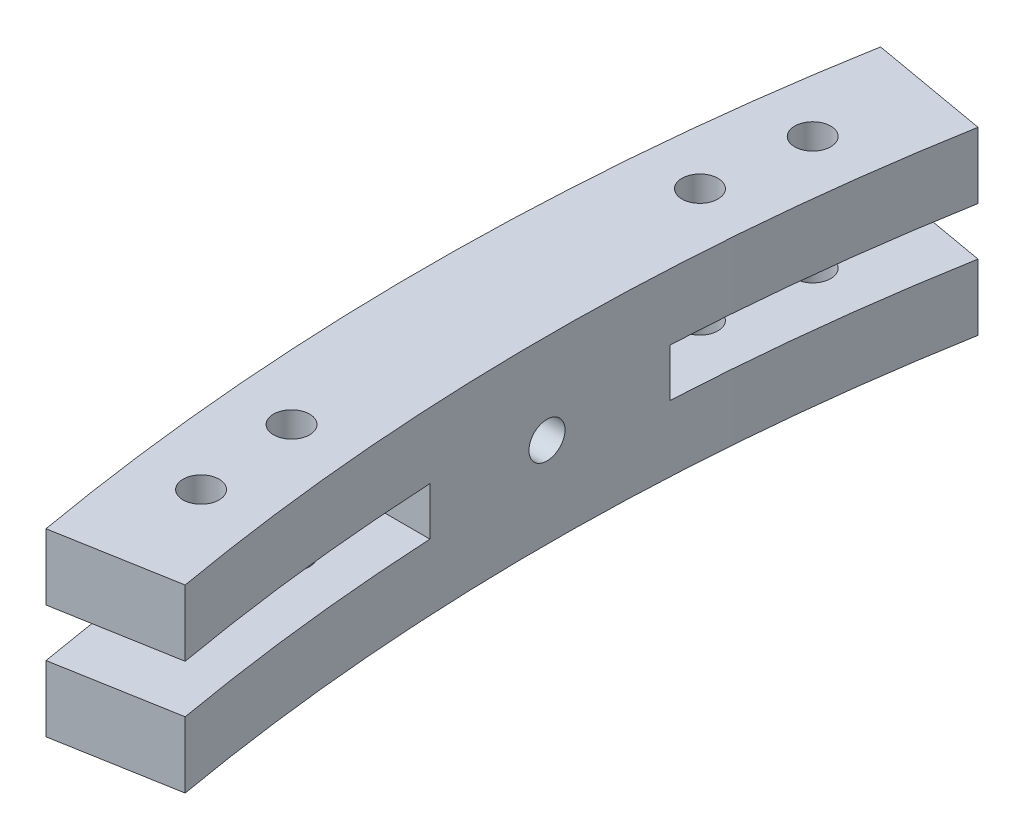
SolidWorks part; units mm, degrees
ref_plane "Front Plane" through (0, 0, 0) normal (0, 0, 1) x (1, 0, 0)
ref_plane "Top Plane" through (0, 0, 0) normal (0, 1, 0) x (1, 0, 0)
ref_plane "Right Plane" through (0, 0, 0) normal (1, 0, 0) x (0, 0, -1)
sketch "Sketch1" plane through (0, 0, 0) normal (0, 0, 1) x (1, 0, 0)
  line L0 (190, 0) -> (-190, 0) construction
  line L1 (0, 190) -> (0, -190) construction
  line L2 (0, 0) -> (-187.1135, 32.9932) construction
  line L3 (0, 0) -> (-187.1135, -32.9932) construction
  line L4 (-187.1135, 32.9932) -> (-196.9616, 34.7296)
  line L5 (-187.1135, -32.9932) -> (-196.9616, -34.7296)
  arc A0 (-187.1135, 32.9932) -> (-187.1135, -32.9932) centre (0, 0) ccw
  arc A1 (-196.9616, 34.7296) -> (-196.9616, -34.7296) centre (0, 0) ccw
  circle A3 centre (0, 0) radius 190 construction
  dimension "D1" = 380
  dimension "D2" = 10
  dimension "D3" = 20
sketch "Sketch9" plane through (0, 0, 0) normal (0, 1, 0) x (1, 0, 0)
  line L0 (0, 0) -> (-196.9616, 34.7296)
  line L1 (-200, 0) -> (200, 0) construction
  line L2 (0, 0) -> (-196.9616, -34.7296)
  circle A0 centre (0, 0) radius 195 construction
  circle A1 centre (0, 0) radius 195 construction
  circle A8 centre (0, 0) radius 200 construction
  circle A9 centre (0, 0) radius 190 construction
  circle A10 centre (0, 0) radius 200
  circle A11 centre (0, 0) radius 190
  dimension "D1" = 20
extrude "base" add sketch "Sketch9" along normal mid plane 15 contours A11 L0 A10 L2
sketch "Sketch11" plane through (0, 0, 0) normal (0, 1, 0) x (1, 0, 0)
  line L8 (-189.7367, -10) -> (-199.7498, -10) construction
  line L9 (-187.1135, -32.9932) -> (-196.9616, -34.7296) construction
  line L10 (-189.7367, 10) -> (-199.7498, 10) construction
  line L11 (-187.1135, 32.9932) -> (-196.9616, 34.7296) construction
  line L12 (-189.7367, -10) -> (-199.7498, -10)
  line L13 (-187.1135, -32.9932) -> (-196.9616, -34.7296)
  line L14 (-189.7367, 10) -> (-199.7498, 10)
  line L15 (-187.1135, 32.9932) -> (-196.9616, 34.7296)
  circle A14 centre (0, 0) radius 200 construction
  circle A15 centre (0, 0) radius 190 construction
  arc A16 (-196.9616, 34.7296) -> (-199.7498, 10) centre (0, 0) ccw
  arc A17 (-187.1135, 32.9932) -> (-189.7367, 10) centre (0, 0) ccw
  arc A18 (-199.7498, -10) -> (-196.9616, -34.7296) centre (0, 0) ccw
  arc A19 (-189.7367, -10) -> (-187.1135, -32.9932) centre (0, 0) ccw
extrude "mount" cut sketch "Sketch11" along normal up to surface and the other way up to surface
sketch "Sketch12" plane through (0, 0, 0) normal (0, 1, 0) x (1, 0, 0)
  line L0 (-200, 0) -> (200, 0) construction
  line L1 (-200, 0) -> (200, 0) construction
  line L2 (0, 0) -> (-193.3317, 25.4526) construction
  line L3 (0, 0) -> (-194.258, 16.9954) construction
  line L4 (0, 0) -> (-194.258, -16.9954) construction
  line L5 (0, 0) -> (-193.3317, -25.4526) construction
  circle A0 centre (0, 0) radius 195 construction
  circle A1 centre (0, 0) radius 195 construction
  circle A2 centre (-193.3317, 25.4526) radius 1.5
  circle A3 centre (-194.258, 16.9954) radius 1.5
  circle A4 centre (-194.258, -16.9954) radius 1.5
  circle A5 centre (-193.3317, -25.4526) radius 1.5
  dimension "D1" = 3
  dimension "D2" = 10
  dimension "D3" = 15
extrude "mount hole" cut sketch "Sketch12" against normal through all both and the other way through all
sketch "Sketch13" plane through (0, 0, 0) normal (0, 1, 0) x (1, 0, 0)
  line L0 (0, 0) -> (-195, 0) construction
  line L1 (-200, 0) -> (200, 0) construction
  line L3 (-193.75, 3) -> (-196.25, 3) construction
  line L4 (-193.75, 3) -> (-193.75, -3) construction
  line L5 (-193.75, -3) -> (-196.25, -3) construction
  line L6 (-196.25, 3) -> (-196.25, -3) construction
  line L7 (-193.75, 3) -> (-196.25, -3) construction
  line L8 (-193.75, -3) -> (-196.25, 3) construction
  line L13 (-196.25, 3) -> (-193.75, 3)
  line L14 (-196.25, 3) -> (-196.25, 0)
  line L15 (-196.25, 0) -> (-193.75, 0)
  line L16 (-193.75, 3) -> (-193.75, 0)
  circle A0 centre (0, 0) radius 195 construction
  dimension "D1" = 2.5
  dimension "D2" = 6
ref_plane "shaft" through (-195, 0, 0) normal (-1, 0, 0) x (0, 0, 1)
sketch "Sketch14" plane through (-195, 0, 0) normal (-1, 0, 0) x (0, 0, 1)
  circle A0 centre (0, 0) radius 1.5
  dimension "D1" = 3
extrude "shaft hole" cut sketch "Sketch14" against normal through all
revolve "bearing hole" cut sketch "Sketch13" angle 360 about L0
